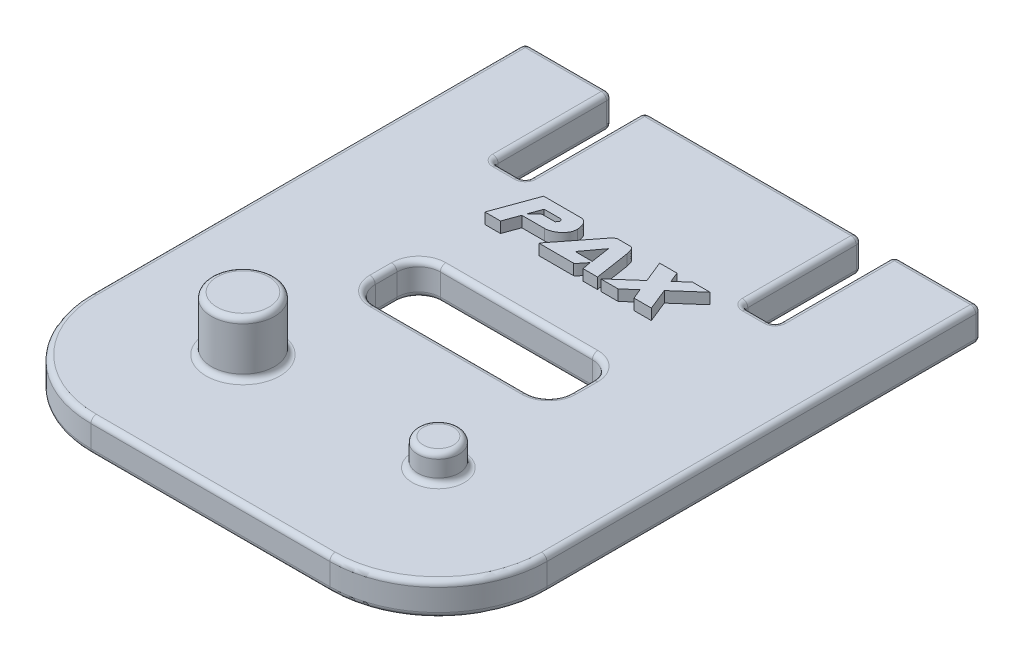
SolidWorks part; units mm, degrees
ref_plane "Front Plane" through (0, 0, 0) normal (0, 0, 1) x (1, 0, 0)
ref_plane "Top Plane" through (0, 0, 0) normal (0, 1, 0) x (1, 0, 0)
ref_plane "Right Plane" through (0, 0, 0) normal (1, 0, 0) x (0, 0, -1)
sketch "Sketch1" plane through (0, 0, 0) normal (0, 1, 0) x (1, 0, 0)
  line L0 (-10, -11) -> (-10, 0)
  line L1 (-10, 0) -> (10, 0)
  line L2 (-21, -50) -> (21, -50)
  line L3 (-10, -11) -> (-13, -11)
  line L4 (-13, -11) -> (-13, 0)
  line L5 (-13, 0) -> (-21, 0)
  line L6 (-21, 0) -> (-21, -50)
  line L7 (0, 0) -> (0, 15.1243) construction
  line L8 (21, 0) -> (21, -50)
  line L9 (13, 0) -> (21, 0)
  line L10 (13, -11) -> (13, 0)
  line L11 (10, -11) -> (13, -11)
  line L13 (10, -11) -> (10, 0)
  dimension "D1" = 11
  dimension "D2" = 10
  dimension "D3" = 3
  dimension "D4" = 8
  dimension "D5" = 50
extrude "Boss-Extrude1" add sketch "Sketch1" along normal blind 3
sketch "Sketch2" plane through (0, 3, 0) normal (0, 1, 0) x (1, 0, 0)
  line L0 (-7.7424, -20.6264) -> (-1.5909, -20.6264)
  line L1 (-1.5909, -20.6264) -> (15.5202, -38.586)
sketch "Sketch4" plane through (0, 3, 0) normal (0, 1, 0) x (1, 0, 0)
  line L0 (-13, 0) -> (-21, 0) construction
  arc A0 (0, -33.6411) -> (0, -42.3589) centre (-9, -38) ccw
  arc A1 (0, -42.3589) -> (0, -33.6411) centre (9, -38) ccw
  dimension "D1" = 20
  dimension "D2" = 20
  dimension "D5" = 9
  dimension "D3" = 38
  dimension "D4" = 18
sketch "Sketch7" plane through (0, 3, 0) normal (0, 1, 0) x (1, 0, 0)
  circle A0 centre (-9, -38) radius 5
  circle A1 centre (9, -38) radius 5
  dimension "D1" = 10
  dimension "D2" = 10
fillet "Fillet1" radius 10 2 edges at (21, 1.5, 50) (-21, 1.5, 50)
sketch "Sketch8" plane through (0, 3, 0) normal (0, 1, 0) x (1, 0, 0)
  circle A0 centre (-9, -38) radius 1.85
  circle A1 centre (9, -38) radius 1.9
  dimension "D1" = 3.7
  dimension "D2" = 3.8
extrude "Boss-Extrude4" add sketch "Sketch8" along normal blind 2.5 contours A1
sketch "Sketch9" plane through (0, 3, 0) normal (0, 1, 0) x (1, 0, 0)
  circle A0 centre (-9, -38) radius 2.9
  dimension "D1" = 5.8
extrude "Boss-Extrude6" add sketch "Sketch9" along normal blind 5
sketch "Sketch10" plane through (0, 3, 0) normal (0, 1, 0) x (1, 0, 0)
  line L0 (-11.2324, -16.4725) -> (10, -16.4725) construction
  text T0 "pax" font "Airstrike" height in points 15
extrude "Boss-Extrude7" add sketch "Sketch10" along normal blind 1
sketch "Sketch11" plane through (0, 3, 0) normal (0, 1, 0) x (1, 0, 0)
  line L1 (-7, -21.8142) -> (7, -21.8142)
  line L2 (-9, -23.8142) -> (-9, -25.8142)
  line L3 (-7, -27.8142) -> (7, -27.8142)
  line L4 (9, -23.8142) -> (9, -25.8142)
  line L5 (-9, -21.8142) -> (9, -27.8142) construction
  line L6 (-9, -27.8142) -> (9, -21.8142) construction
  arc A0 (-9, -25.8142) -> (-7, -27.8142) centre (-7, -25.8142) ccw
  arc A1 (-7, -21.8142) -> (-9, -23.8142) centre (-7, -23.8142) ccw
  arc A2 (7, -21.8142) -> (9, -23.8142) centre (7, -23.8142) cw
  arc A3 (7, -27.8142) -> (9, -25.8142) centre (7, -25.8142) ccw
  point P0 (0, -24.8142)
  dimension "D3" = 2
  dimension "D1" = 6
  dimension "D2" = 18
extrude "Cut-Extrude1" cut sketch "Sketch11" against normal blind 6
fillet "Fillet2" radius 0.5 58 edges at (8.4142, 3, 22.4) (9, 3, 24.8142) (8.4142, 3, 27.2284) (0, 3, 27.8142) (-8.4142, 3, 27.2284) (-9, 3, 24.8142) (-8.4142, 3, 22.4) (-21, 3, 20) (-18.0711, 3, 47.0711) (0, 3, 50) (18.0711, 3, 47.0711) (-21, 0, 20) (-18.0711, 0, 47.0711) (0, 0, 50) (18.0711, 0, 47.0711) (-9, 0, 24.8142) (-8.4142, 0, 22.4) (8.4142, 0, 22.4) (9, 0, 24.8142) (8.4142, 0, 27.2284) (0, 0, 27.8142) (-8.4142, 0, 27.2284) (17, 3, 0) (17, 0, 0) (-17, 3, 0) (-21, 1.5, 0) (-17, 0, 0) (0, 3, 0) (0, 0, 0) (11.5, 3, 11) (11.5, 0, 11) (-11.5, 3, 11) (-11.5, 0, 11) (-10, 1.5, 0) (-10, 3, 5.5) (-10, 1.5, 11) (-10, 0, 5.5) (13, 1.5, 0) (13, 3, 5.5) (13, 1.5, 11) (13, 0, 5.5) (10, 1.5, 11) (10, 3, 5.5) (10, 1.5, 0) (10, 0, 5.5) (-13, 1.5, 11) (-13, 3, 5.5) (-13, 1.5, 0) (-13, 0, 5.5) (-9, 3, 35.1) (-9, 8, 40.9) (9, 3, 36.1) (9, 5.5, 39.9) (0, 3, 21.8142) (0, 0, 21.8142) (21, 1.5, 0) (21, 0, 20) (21, 3, 20)
